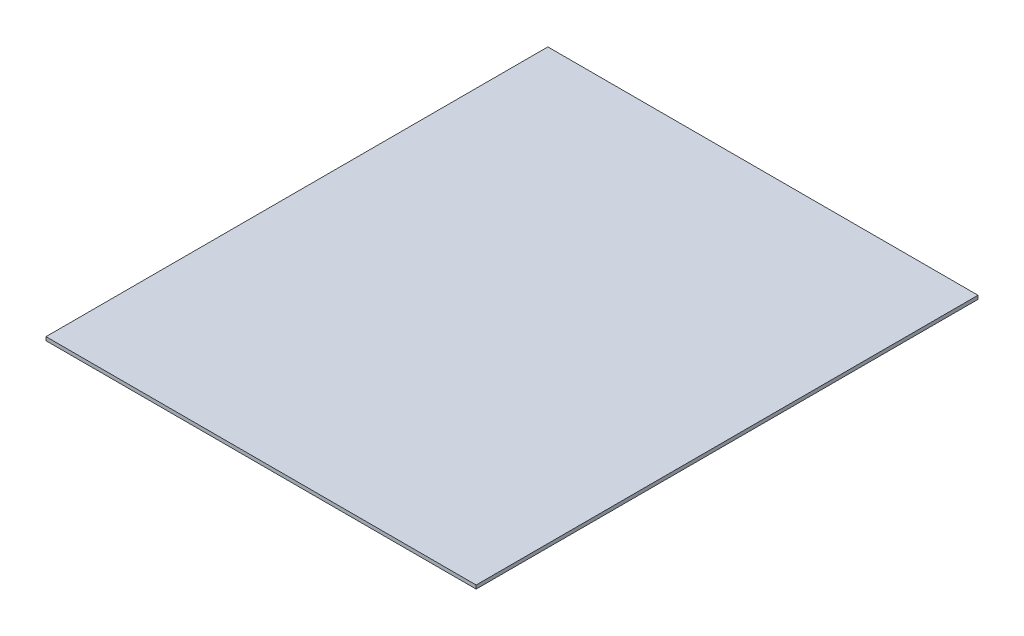
SolidWorks part; units mm, degrees
ref_plane "Front Plane" through (0, 0, 0) normal (0, 0, 1) x (1, 0, 0)
ref_plane "Top Plane" through (0, 0, 0) normal (0, 1, 0) x (1, 0, 0)
ref_plane "Right Plane" through (0, 0, 0) normal (1, 0, 0) x (0, 0, -1)
sketch "Sketch1" plane through (0, 0, 0) normal (0, 1, 0) x (1, 0, 0)
  line L1 (-600, -700) -> (600, -700)
  line L2 (-600, -700) -> (-600, 700)
  line L3 (-600, 700) -> (600, 700)
  line L4 (600, -700) -> (600, 700)
  line L5 (-600, -700) -> (600, 700) construction
  line L6 (-600, 700) -> (600, -700) construction
  point P0 (0, 0)
  dimension "D1" = 1200
  dimension "D2" = 1400
extrude "Boss-Extrude1" add sketch "Sketch1" along normal blind 10
